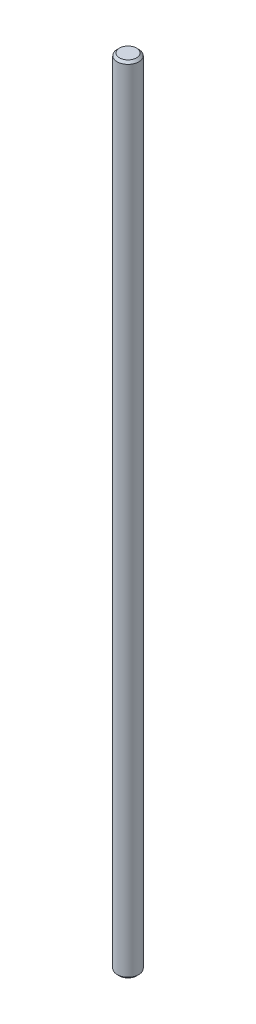
SolidWorks part; units mm, degrees
ref_plane "Front Plane" through (0, 0, 0) normal (0, 0, 1) x (1, 0, 0)
ref_plane "Top Plane" through (0, 0, 0) normal (0, 1, 0) x (1, 0, 0)
ref_plane "Right Plane" through (0, 0, 0) normal (1, 0, 0) x (0, 0, -1)
sketch "m4 diameter sketch" plane through (0, 0, 0) normal (0, 1, 0) x (1, 0, 0)
  circle A0 centre (0, 0) radius 1.9
  dimension "D1" = 3.8
extrude "Boss-Extrude1" add sketch "m4 diameter sketch" along normal blind 140
chamfer "Chamfer1" distance 0.4 angle 45 2 edges at (0, 0, 1.9) (0, 140, 1.9)
